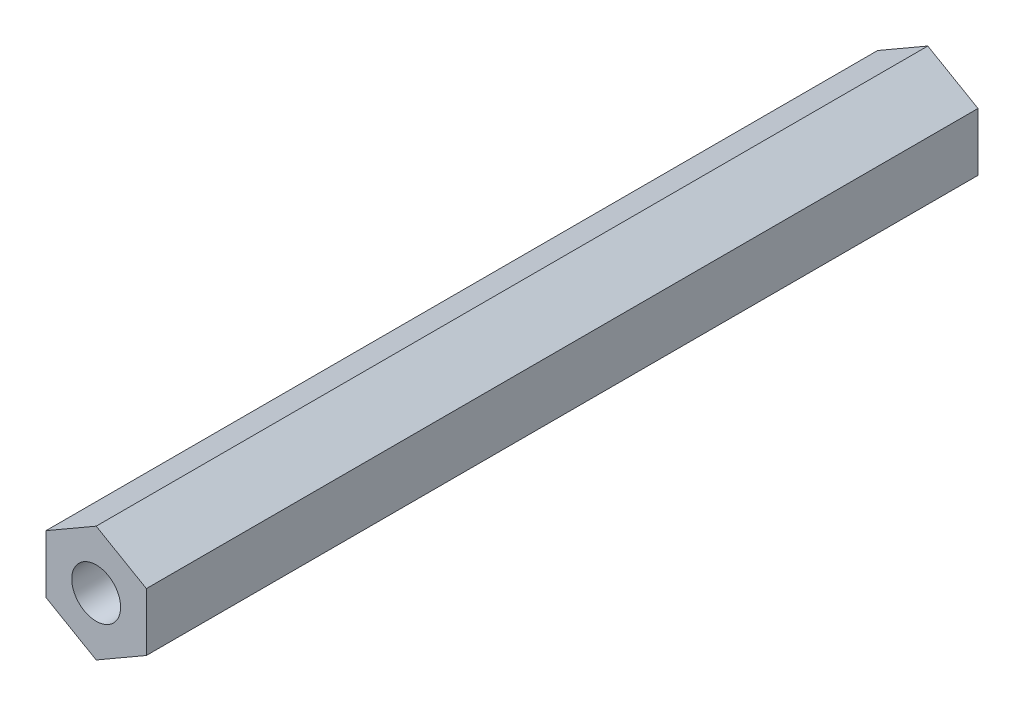
SolidWorks part; units mm, degrees
material "6061-T6 (SS)"
ref_plane "Front" through (0, 0, 0) normal (0, 0, 1) x (1, 0, 0)
ref_plane "Top" through (0, 0, 0) normal (0, 1, 0) x (1, 0, 0)
ref_plane "Right" through (0, 0, 0) normal (1, 0, 0) x (0, 0, -1)
sketch "Sketch2" plane through (0, 0, 0) normal (0, 0, 1) x (1, 0, 0)
  line L1 (0, 6.4158) -> (-5.5562, 3.2079)
  line L2 (-5.5562, 3.2079) -> (-5.5562, -3.2079)
  line L3 (-5.5562, -3.2079) -> (0, -6.4158)
  line L4 (0, -6.4158) -> (5.5563, -3.2079)
  line L5 (5.5563, -3.2079) -> (5.5562, 3.2079)
  line L6 (5.5562, 3.2079) -> (0, 6.4158)
  circle A0 centre (0, 0) radius 5.5562 construction
  dimension "D1" = 11.1125
extrude "Boss-Extrude1" add sketch "Sketch2" along normal mid plane 92.075
sketch "Sketch3" plane through (0, 0, 46.0375) normal (0, 0, 1) x (1, 0, 0)
  circle A0 centre (0, 0) radius 2.7051
  dimension "D1" = 5.4102
extrude "Cut-Extrude1" cut sketch "Sketch3" against normal blind 38.1
sketch "Sketch4" plane through (0, 0, -46.0375) normal (0, 0, -1) x (-1, 0, 0)
  circle A0 centre (0, 0) radius 2.7051
  dimension "D1" = 5.4102
extrude "Cut-Extrude2" cut sketch "Sketch4" against normal blind 38.1
